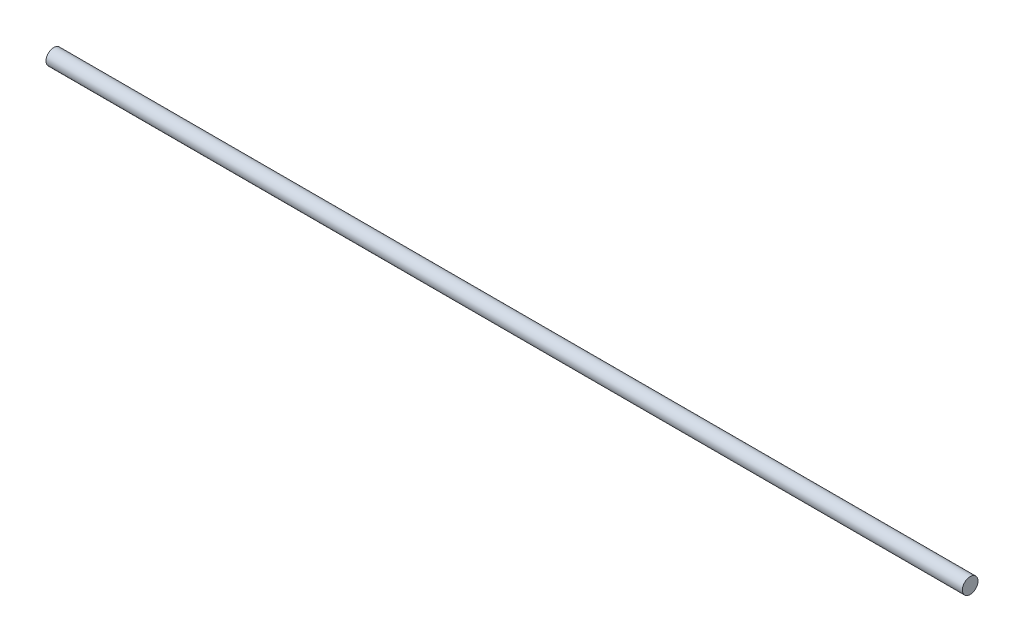
SolidWorks part; units mm, degrees
material "1023 Carbon Steel Sheet (SS)"
ref_plane "Front Plane" through (0, 0, 0) normal (0, 0, 1) x (1, 0, 0)
ref_plane "Top Plane" through (0, 0, 0) normal (0, 1, 0) x (1, 0, 0)
ref_plane "Right Plane" through (0, 0, 0) normal (1, 0, 0) x (0, 0, -1)
sketch "Sketch1" plane through (0, 0, 0) normal (1, 0, 0) x (0, 0, -1)
  circle A0 centre (0, 0) radius 40
  dimension "D1" = 80
extrude "Boss-Extrude1" add sketch "Sketch1" along normal blind 4700
equation "\"d_ho\"= 80"
equation "\"length\"= 4.7m"
equation "\"D1@Sketch1\"=\"d_ho\""
equation "\"D1@Boss-Extrude1\"=\"length\""
